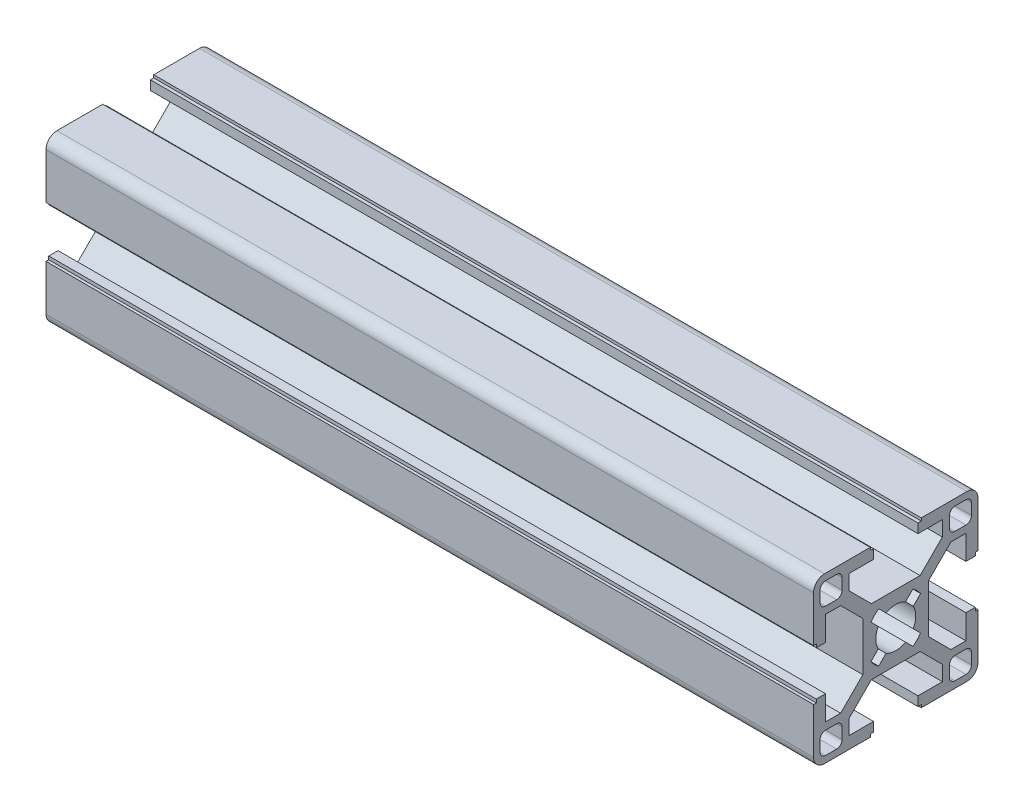
SolidWorks part; units mm, degrees
ref_plane "Ebene vorne" through (0, 0, 0) normal (0, 0, 1) x (1, 0, 0)
ref_plane "Ebene oben" through (0, 0, 0) normal (0, 1, 0) x (1, 0, 0)
ref_plane "Ebene rechts" through (0, 0, 0) normal (1, 0, 0) x (0, 0, -1)
sketch "Skizze1" plane through (0, 0, 0) normal (1, 0, 0) x (0, 0, -1)
  line L0 (8.5, 10.0556) -> (4.4444, 6)
  line L1 (13, 15) -> (-13, 15)
  line L2 (15, 13) -> (15, -13)
  line L3 (13, -15) -> (-13, -15)
  line L4 (-15, 13) -> (-15, -13)
  line L5 (15, 15) -> (-15, -15) construction
  line L6 (15, -15) -> (-15, 15) construction
  line L7 (6, 6) -> (-6, 6)
  line L8 (6, 6) -> (6, -6)
  line L9 (6, -6) -> (-6, -6)
  line L10 (-6, 6) -> (-6, -6)
  line L11 (6, 6) -> (-6, -6) construction
  line L12 (6, -6) -> (-6, 6) construction
  line L13 (8.5, 12.8) -> (-8.5, 12.8)
  line L14 (8.5, 12.8) -> (8.5, 6)
  line L15 (8.5, 6) -> (-8.5, 6)
  line L16 (-8.5, 12.8) -> (-8.5, 6)
  line L17 (4.05, 15) -> (-4.05, 15)
  line L18 (4.05, 15) -> (4.05, 12.8)
  line L19 (4.05, 12.8) -> (-4.05, 12.8)
  line L20 (-4.05, 15) -> (-4.05, 12.8)
  line L21 (-8.5, 10.0556) -> (-4.4444, 6)
  line L22 (3.1172, 4.5314) -> (1.7751, 3.1893)
  line L23 (-3.1172, 4.5314) -> (-1.7751, 3.1893)
  line L24 (15, -4.05) -> (12.8, -4.05)
  line L25 (4.05, 15) -> (4.6516, 15)
  line L26 (4.05, 15) -> (4.05, 14.5)
  line L27 (4.05, 14.5) -> (4.6516, 14.5)
  line L28 (4.6516, 15) -> (4.6516, 14.5)
  line L29 (-4.05, 15) -> (-4.6516, 15)
  line L30 (-4.05, 15) -> (-4.05, 14.5)
  line L31 (-4.05, 14.5) -> (-4.6516, 14.5)
  line L32 (-4.6516, 15) -> (-4.6516, 14.5)
  line L33 (15, -4.6516) -> (14.5, -4.6516)
  line L34 (14.5, -4.05) -> (14.5, -4.6516)
  line L35 (14.5, 4.05) -> (14.5, 4.6516)
  line L36 (15, 4.6516) -> (14.5, 4.6516)
  line L37 (15, 4.05) -> (12.8, 4.05)
  line L38 (12.8, 8.5) -> (6, 8.5)
  line L39 (12.8, -8.5) -> (12.8, 8.5)
  line L40 (12.8, -8.5) -> (6, -8.5)
  line L41 (10.0556, -8.5) -> (6, -4.4444)
  line L42 (10.0556, 8.5) -> (6, 4.4444)
  line L43 (4.5314, -3.1172) -> (3.1893, -1.7751)
  line L44 (4.5314, 3.1172) -> (3.1893, 1.7751)
  line L45 (-4.05, -15) -> (-4.05, -12.8)
  line L46 (-4.6516, -15) -> (-4.6516, -14.5)
  line L47 (-4.05, -14.5) -> (-4.6516, -14.5)
  line L48 (4.05, -14.5) -> (4.6516, -14.5)
  line L49 (4.6516, -15) -> (4.6516, -14.5)
  line L50 (4.05, -15) -> (4.05, -12.8)
  line L51 (8.5, -12.8) -> (8.5, -6)
  line L52 (-8.5, -12.8) -> (8.5, -12.8)
  line L53 (-8.5, -12.8) -> (-8.5, -6)
  line L54 (-8.5, -10.0556) -> (-4.4444, -6)
  line L55 (8.5, -10.0556) -> (4.4444, -6)
  line L56 (-3.1172, -4.5314) -> (-1.7751, -3.1893)
  line L57 (3.1172, -4.5314) -> (1.7751, -3.1893)
  line L58 (-15, 4.05) -> (-12.8, 4.05)
  line L59 (-15, 4.6516) -> (-14.5, 4.6516)
  line L60 (-14.5, 4.05) -> (-14.5, 4.6516)
  line L61 (-14.5, -4.05) -> (-14.5, -4.6516)
  line L62 (-15, -4.6516) -> (-14.5, -4.6516)
  line L63 (-15, -4.05) -> (-12.8, -4.05)
  line L64 (-12.8, -8.5) -> (-6, -8.5)
  line L65 (-12.8, 8.5) -> (-12.8, -8.5)
  line L66 (-12.8, 8.5) -> (-6, 8.5)
  line L67 (-10.0556, 8.5) -> (-6, 4.4444)
  line L68 (-10.0556, -8.5) -> (-6, -4.4444)
  line L69 (-4.5314, 3.1172) -> (-3.1893, 1.7751)
  line L70 (-4.5314, -3.1172) -> (-3.1893, -1.7751)
  line L71 (6, -8.5) -> (6, 8.5)
  line L72 (-8.5, -6) -> (8.5, -6)
  line L73 (-6, 8.5) -> (-6, -8.5)
  line L75 (12.8, 13.8) -> (10.8, 13.8)
  line L76 (13.8, 12.8) -> (13.8, 10.8)
  line L77 (12.8, 9.8) -> (10.8, 9.8)
  line L78 (9.8, 12.8) -> (9.8, 10.8)
  line L79 (13.8, 13.8) -> (9.8, 9.8) construction
  line L80 (13.8, 9.8) -> (9.8, 13.8) construction
  line L81 (-10.8, 13.8) -> (-12.8, 13.8)
  line L82 (-9.8, 12.8) -> (-9.8, 10.8)
  line L83 (-10.8, 9.8) -> (-12.8, 9.8)
  line L84 (-13.8, 12.8) -> (-13.8, 10.8)
  line L85 (-9.8, 13.8) -> (-13.8, 9.8) construction
  line L86 (-9.8, 9.8) -> (-13.8, 13.8) construction
  line L87 (12.8, -9.8) -> (10.8, -9.8)
  line L88 (13.8, -10.8) -> (13.8, -12.8)
  line L89 (12.8, -13.8) -> (10.8, -13.8)
  line L90 (9.8, -10.8) -> (9.8, -12.8)
  line L91 (13.8, -9.8) -> (9.8, -13.8) construction
  line L92 (13.8, -13.8) -> (9.8, -9.8) construction
  line L93 (-10.8, -9.8) -> (-12.8, -9.8)
  line L94 (-9.8, -10.8) -> (-9.8, -12.8)
  line L95 (-10.8, -13.8) -> (-12.8, -13.8)
  line L96 (-13.8, -10.8) -> (-13.8, -12.8)
  line L97 (-9.8, -9.8) -> (-13.8, -13.8) construction
  line L98 (-9.8, -13.8) -> (-13.8, -9.8) construction
  arc A0 (13, -15) -> (15, -13) centre (13, -13) ccw
  arc A1 (-13, -15) -> (-15, -13) centre (-13, -13) cw
  arc A2 (-15, 13) -> (-13, 15) centre (-13, 13) cw
  arc A3 (13, 15) -> (15, 13) centre (13, 13) cw
  circle A4 centre (0, 0) radius 3.65
  circle A5 centre (0, 0) radius 5.5
  circle A6 centre (0, 0) radius 3.65
  circle A7 centre (0, 0) radius 3.65
  circle A8 centre (0, 0) radius 3.65
  arc A9 (12.8, -13.8) -> (13.8, -12.8) centre (12.8, -12.8) ccw
  arc A10 (13.8, -10.8) -> (12.8, -9.8) centre (12.8, -10.8) ccw
  arc A11 (9.8, -12.8) -> (10.8, -13.8) centre (10.8, -12.8) ccw
  arc A12 (9.8, -10.8) -> (10.8, -9.8) centre (10.8, -10.8) cw
  arc A13 (-10.8, -13.8) -> (-9.8, -12.8) centre (-10.8, -12.8) ccw
  arc A14 (-10.8, -9.8) -> (-9.8, -10.8) centre (-10.8, -10.8) cw
  arc A15 (-13.8, -12.8) -> (-12.8, -13.8) centre (-12.8, -12.8) ccw
  arc A16 (-13.8, -10.8) -> (-12.8, -9.8) centre (-12.8, -10.8) cw
  arc A17 (-12.8, 9.8) -> (-13.8, 10.8) centre (-12.8, 10.8) cw
  arc A18 (-10.8, 9.8) -> (-9.8, 10.8) centre (-10.8, 10.8) ccw
  arc A19 (-13.8, 12.8) -> (-12.8, 13.8) centre (-12.8, 12.8) cw
  arc A20 (-10.8, 13.8) -> (-9.8, 12.8) centre (-10.8, 12.8) cw
  arc A21 (13.8, 10.8) -> (12.8, 9.8) centre (12.8, 10.8) cw
  arc A22 (10.8, 9.8) -> (9.8, 10.8) centre (10.8, 10.8) cw
  arc A23 (10.8, 13.8) -> (9.8, 12.8) centre (10.8, 12.8) ccw
  arc A24 (12.8, 13.8) -> (13.8, 12.8) centre (12.8, 12.8) cw
  point P0 (0, 0)
  point P33 (0, 12.8)
  point P34 (0, 15)
  point P36 (0, 12.8)
  point P50 (11.8, 11.8)
  point P122 (0, 0)
  point P125 (-11.8, 11.8)
  point P129 (0, 0)
  point P131 (11.8, -11.8)
  point P136 (-11.8, -11.8)
  dimension "D2" = 2
  dimension "D3" = 7.3
  dimension "D4" = 11
  dimension "D20" = 1
  dimension "D1" = 30
  dimension "D5" = 12
  dimension "D6" = 17
  dimension "D7" = 8.1
  dimension "D8" = 2.2
  dimension "D9" = 9
  dimension "D10" = 1.1
  dimension "D11" = 1.1
  dimension "D12" = 1
  dimension "D13" = 1
  dimension "D14" = 0.5
  dimension "D15" = 0.6016
  dimension "D18" = 4
  dimension "D19" = 1.2
  dimension "D16" = 4
  dimension "D17" = 4
extrude "Aufsatz-Linear austragen1" add sketch "Skizze1" along normal blind 140 contours A3 L1 L28 L27 L18 L13 L14 L38 L39 L37 L35 L36 L2 | L42 L38 L14 | L71 L15 L42 L14 L38 L0 | L42 L15 L8 | L7 L71 L0 | L38 L14 L0 | L7 L15 L10 L9 L8 A5 | L43 A5 L44 A4 | L22 A5 L23 A4 | L69 A5 L70 A4 | L56 A5 L57 A4 | L3 A0 L2 L33 L34 L24 L39 L40 L51 L52 L50 L48 L49 | L51 L40 L41 | L72 L71 L55 L40 L51 L41 | L8 L72 L41 | L55 L71 L9 | L55 L51 L40 | L73 L72 L68 L53 L64 L54 | L68 L72 L10 | L9 L73 L54 | L68 L64 L53 | L64 L53 L54 | A1 L3 L46 L47 L45 L52 L53 L64 L65 L63 L61 L62 L4 | A2 L4 L59 L60 L58 L65 L66 L16 L13 L20 L31 L32 L1 | L66 L67 L16 | L16 L66 L21 | L73 L21 L66 L16 L67 L15 | L21 L73 L15 | L15 L67 L10
